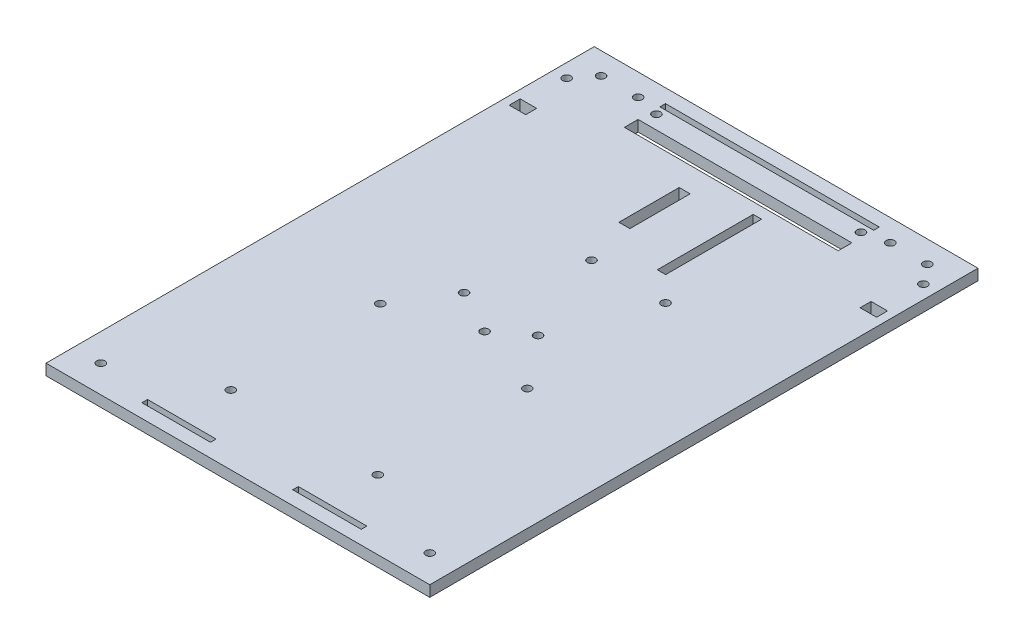
SolidWorks part; units mm, degrees
ref_plane "Front Plane" through (0, 0, 0) normal (0, 0, 1) x (1, 0, 0)
ref_plane "Top Plane" through (0, 0, 0) normal (0, 1, 0) x (1, 0, 0)
ref_plane "Right Plane" through (0, 0, 0) normal (1, 0, 0) x (0, 0, -1)
sketch "Sketch1" plane through (0, 0, 0) normal (0, 1, 0) x (1, 0, 0)
  line L1 (70, -100) -> (-70, -100)
  line L2 (70, -100) -> (70, 100)
  line L3 (70, 100) -> (-70, 100)
  line L4 (-70, -100) -> (-70, 100)
  line L5 (70, -100) -> (-70, 100) construction
  line L6 (70, 100) -> (-70, -100) construction
  point P0 (0, 0)
  dimension "D1" = 140
  dimension "D2" = 200
extrude "Boss-Extrude1" add sketch "Sketch1" along normal blind 4
sketch "Sketch2" plane through (0, 4, 0) normal (0, 1, 0) x (1, 0, 0)
  line L0 (0, 100) -> (0, -100) construction
  line L1 (70, 100) -> (-70, 100) construction
  line L2 (-70, -100) -> (70, -100) construction
  line L3 (0, 0) -> (-70, 0) construction
  line L4 (-70, 100) -> (-70, -100) construction
  line L6 (39, 80) -> (-39, 80)
  line L7 (39, 80) -> (39, 100)
  line L8 (39, 100) -> (-39, 100)
  line L9 (-39, 80) -> (-39, 100)
  line L10 (39, 80) -> (-39, 100) construction
  line L11 (39, 100) -> (-39, 80) construction
  line L12 (39, 92.95) -> (-39, 92.95)
  line L13 (39, 92.95) -> (39, 95)
  line L14 (39, 95) -> (-39, 95)
  line L15 (-39, 92.95) -> (-39, 95)
  line L16 (39, 92.95) -> (-39, 95) construction
  line L17 (39, 95) -> (-39, 92.95) construction
  line L18 (39, 80) -> (-39, 80)
  line L19 (39, 80) -> (39, 85)
  line L20 (39, 85) -> (-39, 85)
  line L21 (-39, 80) -> (-39, 85)
  line L22 (39, 80) -> (-39, 85) construction
  line L23 (39, 85) -> (-39, 80) construction
  circle A0 centre (-37.3, 90) radius 1.5
  circle A1 centre (37.3, 90) radius 1.5
  point P11 (0, 90)
  point P20 (0, 93.975)
  point P25 (0, 82.5)
  dimension "D3" = 3
  dimension "D4" = 1.7
  dimension "D5" = 10
  dimension "D1" = 20
  dimension "D2" = 78
  dimension "D6" = 2.05
  dimension "D7" = 5
  dimension "D8" = 5
  dimension "D9" = 0
extrude "Cut-Extrude3" cut sketch "Sketch2" against normal through all contours L7 L14 L9 L12 | A0 | A1 | L7 L20 L9 L18
sketch "Sketch3" plane through (0, 4, 0) normal (0, 1, 0) x (1, 0, 0)
  line L0 (70, 100) -> (-70, 100) construction
  line L1 (-70.056, 95) -> (-60.056, 95)
  line L2 (-70.056, 95) -> (-70.056, 60)
  line L3 (-70.056, 60) -> (-60.056, 60)
  line L4 (-60.056, 95) -> (-60.056, 60)
  line L5 (-70.056, 95) -> (-60.056, 60) construction
  line L6 (-70.056, 60) -> (-60.056, 95) construction
  line L7 (-39, 80) -> (-39, 85) construction
  line L8 (0, 0) -> (0, 100) construction
  line L9 (-70, 100) -> (-70, -100) construction
  line L10 (-61, 66) -> (-67, 66)
  line L11 (-61, 66) -> (-61, 70)
  line L12 (-61, 70) -> (-67, 70)
  line L13 (-67, 66) -> (-67, 70)
  line L14 (-61, 66) -> (-67, 70) construction
  line L15 (-61, 70) -> (-67, 66) construction
  line L16 (61, 66) -> (61, 70)
  line L17 (61, 66) -> (67, 66)
  line L18 (67, 66) -> (67, 70)
  line L19 (61, 70) -> (67, 70)
  line L20 (70.056, 60) -> (60.056, 60)
  line L21 (70.056, 95) -> (70.056, 60)
  line L22 (70.056, 95) -> (60.056, 95)
  line L23 (60.056, 95) -> (60.056, 60)
  circle A0 centre (-65.056, 85) radius 1.5
  circle A1 centre (65.056, 85) radius 1.5
  point P0 (-65.056, 77.5)
  point P11 (-64, 68)
  dimension "D5" = 3
  dimension "D6" = 10
  dimension "D7" = 5
  dimension "D8" = 15
  dimension "D1" = 35
  dimension "D2" = 10
  dimension "D3" = 5
  dimension "D4" = 21.056
  dimension "D9" = 4
  dimension "D10" = 6
  dimension "D11" = 3
extrude "Cut-Extrude5" cut sketch "Sketch3" against normal through all contours L13 L10 L11 L12 | A1 | L19 L16 L17 L18 | A0
sketch "Sketch4" plane through (0, 4, 0) normal (0, 1, 0) x (1, 0, 0)
  line L0 (-70, 100) -> (-70, -100) construction
  line L1 (70, 100) -> (-70, 100) construction
  line L2 (0, 0) -> (0, 100) construction
  circle A0 centre (-46, 92) radius 1.5
  circle A1 centre (-59.5, 92) radius 1.5
  circle A2 centre (46, 92) radius 1.5
  circle A3 centre (59.5, 92) radius 1.5
  dimension "D1" = 3
  dimension "D2" = 3
  dimension "D4" = 10.5
  dimension "D5" = 8
  dimension "D6" = 8
  dimension "D3" = 13.5
extrude "Cut-Extrude6" cut sketch "Sketch4" against normal through all contours A3 | A1 | A0 | A2
sketch "Sketch6" plane through (0, 4, 0) normal (0, 1, 0) x (1, 0, 0)
  line L0 (0, 0) -> (0, 100) construction
  line L1 (70, 100) -> (-70, 100) construction
  line L3 (12, 76) -> (15.05, 76)
  line L4 (12, 76) -> (12, 41)
  line L5 (12, 41) -> (15.05, 41)
  line L6 (15.05, 76) -> (15.05, 41)
  line L7 (12, 76) -> (15.05, 41) construction
  line L8 (12, 41) -> (15.05, 76) construction
  line L9 (-10, 71) -> (-6, 71)
  line L10 (-10, 71) -> (-10, 49)
  line L11 (-10, 49) -> (-6, 49)
  line L12 (-6, 71) -> (-6, 49)
  line L13 (-10, 71) -> (-6, 49) construction
  line L14 (-10, 49) -> (-6, 71) construction
  point P5 (13.525, 58.5)
  point P10 (-8, 60)
  dimension "D1" = 24
  dimension "D2" = 3.05
  dimension "D3" = 35
  dimension "D4" = 12
  dimension "D5" = 10
  dimension "D6" = 4
  dimension "D7" = 22
  dimension "D8" = 5
extrude "Cut-Extrude13" cut sketch "Sketch6" against normal blind 4
sketch "Sketch7" plane through (0, 4, 0) normal (0, 1, 0) x (1, 0, 0)
  line L0 (-70, 100) -> (-70, -100) construction
  line L1 (70, -88) -> (-70, -88)
  line L2 (70, -88) -> (70, -58)
  line L3 (70, -58) -> (-70, -58)
  line L4 (-70, -88) -> (-70, -58)
  line L5 (70, -88) -> (-70, -58) construction
  line L6 (70, -58) -> (-70, -88) construction
  line L8 (-70, -100) -> (70, -100) construction
  line L10 (0, 0) -> (0, 100) construction
  line L11 (-55, -56) -> (-30, -56)
  line L12 (-55, -56) -> (-55, 49)
  line L13 (-55, 49) -> (-30, 49)
  line L14 (-30, -56) -> (-30, 49)
  line L15 (-55, -56) -> (-30, 49) construction
  line L16 (-55, 49) -> (-30, -56) construction
  line L17 (70, 100) -> (-70, 100) construction
  line L18 (55, -56) -> (30, -56)
  line L19 (30, -56) -> (30, 49)
  line L20 (55, 49) -> (30, 49)
  line L21 (55, -56) -> (55, 49)
  line L23 (26, -6) -> (1, -6)
  line L24 (28, -77) -> (-30, -77)
  line L25 (28, -77) -> (28, -18)
  line L26 (28, -18) -> (-30, -18)
  line L27 (-30, -77) -> (-30, -18)
  line L28 (28, -77) -> (-30, -18) construction
  line L29 (28, -18) -> (-30, -77) construction
  line L30 (-26, 36.5) -> (-1, 36.5)
  line L31 (-26, 36.5) -> (-26, -6)
  line L32 (-26, -6) -> (-1, -6)
  line L33 (-1, 36.5) -> (-1, -6)
  line L34 (-26, 36.5) -> (-1, -6) construction
  line L35 (-26, -6) -> (-1, 36.5) construction
  line L36 (1, 36.5) -> (1, -6)
  line L37 (26, 36.5) -> (26, -6)
  line L38 (26, 36.5) -> (1, 36.5)
  line L39 (-1, -47.5) -> (-1, -18) construction
  line L40 (-1, -47.5) -> (30, -47.5) construction
  circle A0 centre (-27.8021, -20.2358) radius 1.5
  circle A1 centre (25.8021, -20.2358) radius 1.5
  circle A2 centre (25.8021, -74.7642) radius 1.5
  circle A3 centre (-27.8021, -74.7642) radius 1.5
  circle A4 centre (-3, 32) radius 1.5
  circle A5 centre (-16, -1.5) radius 1.5
  circle A6 centre (11, -1.5) radius 1.5
  circle A7 centre (24, 32) radius 1.5
  point P0 (0, -73)
  point P13 (-42.5, -3.5)
  point P27 (-1, -47.5)
  point P32 (-13.5, 15.25)
  dimension "D15" = 3
  dimension "D17" = 3
  dimension "D19" = 2
  dimension "D20" = 3
  dimension "D18" = 4.5
  dimension "D21" = 4.5
  dimension "D22" = 10
  dimension "D23" = 3
  dimension "D26" = 3
  dimension "D27" = 4.5
  dimension "D28" = 10
  dimension "D1" = 30
  dimension "D2" = 12
  dimension "D3" = 140
  dimension "D4" = 25
  dimension "D5" = 105
  dimension "D6" = 2
  dimension "D7" = 15
  dimension "D8" = 59
  dimension "D9" = 40
  dimension "D10" = 58
  dimension "D11" = 42.5
  dimension "D12" = 25
  dimension "D13" = 4
  dimension "D14" = 12
  dimension "D16" = 2.2358
  dimension "D24" = 2
  dimension "D25" = 4.5
extrude "Cut-Extrude15" cut sketch "Sketch7" against normal through all contours A1 | A3 | A2 | A7 | A6 | A5 | A4 | A0
sketch "Sketch8" plane through (0, 4, 0) normal (0, 1, 0) x (1, 0, 0)
  line L0 (-70, 100) -> (-70, -100) construction
  line L7 (-70, -100) -> (70, -100) construction
  line L8 (0, 0) -> (0, 100) construction
  line L9 (70, 100) -> (-70, 100) construction
  line L15 (15, -95) -> (15, -92.95)
  line L16 (-40, -95) -> (-15, -95)
  line L17 (-40, -95) -> (-40, -92.95)
  line L18 (-40, -92.95) -> (-15, -92.95)
  line L19 (-15, -95) -> (-15, -92.95)
  line L20 (-40, -95) -> (-15, -92.95) construction
  line L21 (-40, -92.95) -> (-15, -95) construction
  line L22 (40, -95) -> (15, -95)
  line L23 (40, -95) -> (40, -92.95)
  line L24 (40, -92.95) -> (15, -92.95)
  circle A0 centre (0, -10) radius 1.5
  circle A1 centre (-60, -90) radius 1.5
  circle A2 centre (60, -90) radius 1.5
  point P26 (-27.5, -93.975)
  dimension "D5" = 3
  dimension "D8" = 3
  dimension "D9" = 10
  dimension "D10" = 10
  dimension "D6" = 90
  dimension "D11" = 2.05
  dimension "D12" = 30
  dimension "D13" = 25
  dimension "D14" = 5
extrude "Cut-Extrude16" cut sketch "Sketch8" against normal blind 4
